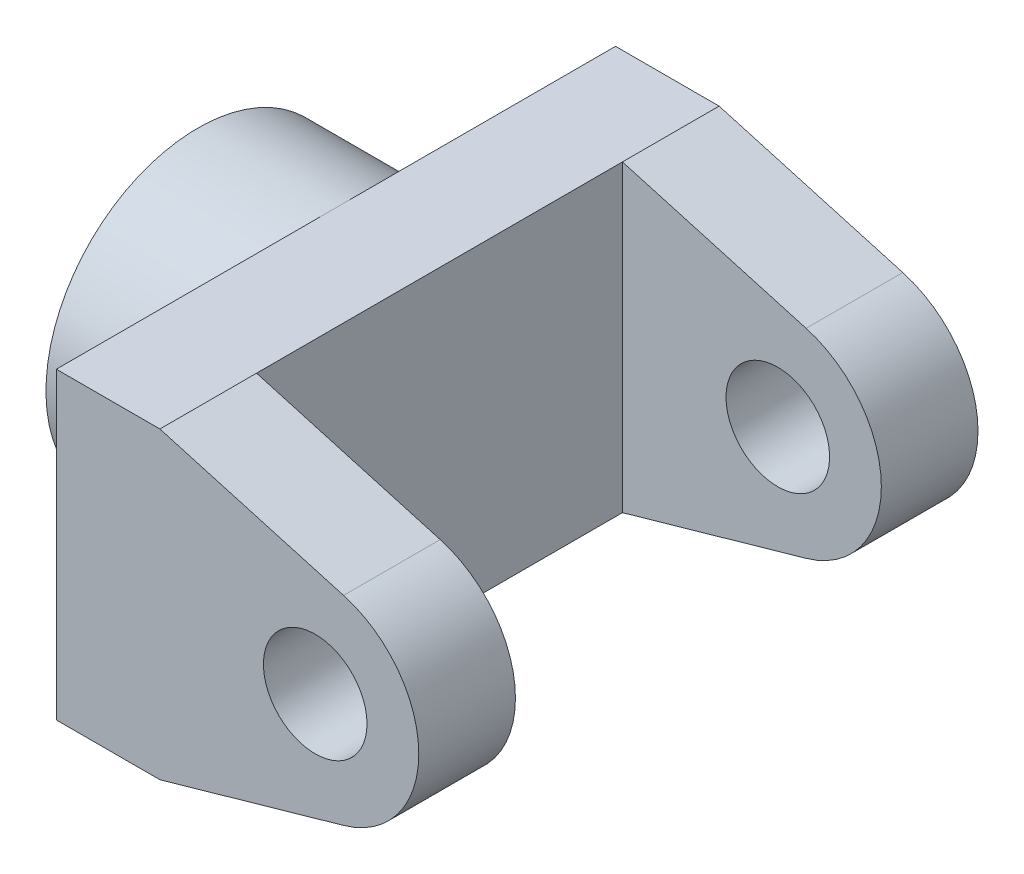
SolidWorks part; units mm, degrees
ref_plane "Front" through (0, 0, 0) normal (0, 0, 1) x (1, 0, 0)
ref_plane "Top" through (0, 0, 0) normal (0, 1, 0) x (1, 0, 0)
ref_plane "Right" through (0, 0, 0) normal (1, 0, 0) x (0, 0, -1)
sketch "Sketch2" plane through (0, 0, 0) normal (0, 0, 1) x (1, 0, 0)
  line L0 (-75, -44) -> (-75, 44)
  line L1 (0, 0) -> (-86.7621, 0) construction
  line L2 (-45, -44) -> (-45, 44)
  line L3 (-75, 44) -> (-45, 44)
  line L4 (-45, 44) -> (8.2128, 28.854)
  line L5 (-75, -44) -> (-45, -44)
  line L6 (-45, -44) -> (8.2128, -28.854)
  circle A0 centre (0, 0) radius 15
  arc A1 (4.5356, -29.6552) -> (4.5356, 29.6552) centre (0, 0) ccw
  circle A2 centre (0, 0) radius 30
  point P6 (-45, 0)
  point P7 (-75, 0)
  point P9 (-75, 0)
  point P15 (-45, 0)
  dimension "D1" = 30
  dimension "D2" = 60
  dimension "D7" = 60
  dimension "D3" = 30
  dimension "D4" = 75
  dimension "D5" = 88
  dimension "D6" = 88
extrude "Boss-Extrude1" add sketch "Sketch2" along normal blind 162
sketch "Sketch3" plane through (0, -44, 0) normal (0, -1, 0) x (1, 0, 0)
  line L0 (-45, 162) -> (-45, 0) construction
  line L1 (-45, 134) -> (30, 134)
  line L2 (-45, 134) -> (-45, 28)
  line L3 (-45, 28) -> (30, 28)
  line L4 (30, 134) -> (30, 28)
  line L5 (30, 0) -> (30, 162) construction
  line L6 (-75, 162) -> (-75, 0) construction
  point P10 (-75, 81)
  point P11 (-45, 81)
  dimension "D1" = 106
extrude "Cut-Extrude1" cut sketch "Sketch3" against normal through all
sketch "Sketch4" plane through (-75, 0, 0) normal (-1, 0, 0) x (0, 0, 1)
  line L0 (0, -44) -> (0, 44) construction
  circle A0 centre (81, 0) radius 44
  circle A1 centre (81, 0) radius 25
  point P3 (37.0051, -0.667)
  dimension "D1" = 88
  dimension "D2" = 50
  dimension "D3" = 81
extrude "Boss-Extrude2" add sketch "Sketch4" along normal blind 40
sketch "Sketch7" plane through (-115, 0, 0) normal (-1, 0, 0) x (0, 0, 1)
  line L1 (56.3221, -4) -> (50.0691, -4)
  line L3 (56.3221, 4) -> (50.0691, 4)
  line L4 (50.0691, -4) -> (50.0691, 4)
  line L5 (56, 0) -> (50.0691, 4) construction
  line L6 (56, 0) -> (50.0691, -4) construction
  circle A0 centre (81, 0) radius 25 construction
  circle A1 centre (81, 0) radius 25
  point P0 (56, 0)
  circle M4 centre (81, 0) radius 25
  dimension "D2" = 8
extrude "Cut-Extrude5" cut sketch "Sketch7" against normal blind 60 contours L4 L1 L3 M4
scale "Scale1" scale about centroid uniform scaling yes scale factor 0.33
